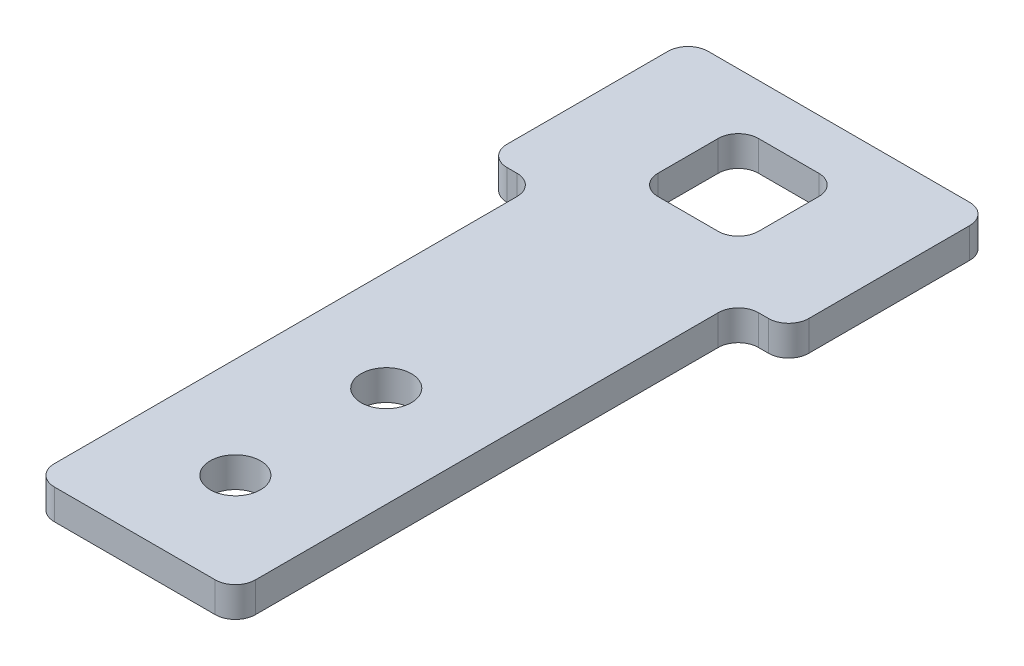
SolidWorks part; units mm, degrees
ref_plane "前视基准面" through (0, 0, 0) normal (0, 0, 1) x (1, 0, 0)
ref_plane "上视基准面" through (0, 0, 0) normal (0, 1, 0) x (1, 0, 0)
ref_plane "右视基准面" through (0, 0, 0) normal (1, 0, 0) x (0, 0, -1)
sketch "草图1" plane through (0, 0, 0) normal (0, 1, 0) x (1, 0, 0)
  line L0 (22, 50) -> (23, 50)
  line L1 (0, 70) -> (20, 70)
  line L2 (0, 48) -> (0, 2)
  line L3 (2, 0) -> (18, 0)
  line L4 (20, 48) -> (20, 2)
  line L5 (-3, 70) -> (23, 70)
  line L6 (-5, 68) -> (-5, 52)
  line L7 (-3, 50) -> (-2, 50)
  line L8 (25, 68) -> (25, 52)
  line L10 (7, 65) -> (13, 65)
  line L11 (5, 63) -> (5, 57)
  line L12 (7, 55) -> (13, 55)
  line L13 (15, 63) -> (15, 57)
  circle A0 centre (10, 25) radius 2.5
  circle A1 centre (10, 10) radius 2.5
  arc A2 (25, 68) -> (23, 70) centre (23, 68) ccw
  arc A3 (23, 50) -> (25, 52) centre (23, 52) ccw
  arc A4 (20, 48) -> (22, 50) centre (22, 48) cw
  arc A5 (18, 0) -> (20, 2) centre (18, 2) ccw
  arc A6 (0, 2) -> (2, 0) centre (2, 2) ccw
  arc A7 (-2, 50) -> (0, 48) centre (-2, 48) cw
  arc A8 (-5, 52) -> (-3, 50) centre (-3, 52) ccw
  arc A9 (-3, 70) -> (-5, 68) centre (-3, 68) ccw
  arc A10 (15, 63) -> (13, 65) centre (13, 63) ccw
  arc A11 (13, 55) -> (15, 57) centre (13, 57) ccw
  arc A12 (7, 55) -> (5, 57) centre (7, 57) cw
  arc A13 (5, 63) -> (7, 65) centre (7, 63) cw
  point P21 (25, 70)
  point P30 (0, 0)
  point P35 (-5, 50)
  point P38 (-5, 70)
  point P41 (15, 65)
  point P46 (5, 55)
  point P49 (5, 65)
  dimension "D10" = 5
  dimension "D12" = 5
  dimension "D16" = 2
  dimension "D17" = 2
  dimension "D1" = 20
  dimension "D2" = 70
  dimension "D3" = 30
  dimension "D4" = 20
  dimension "D5" = 5
  dimension "D6" = 10
  dimension "D7" = 10
  dimension "D8" = 5
  dimension "D9" = 10
  dimension "D11" = 10
  dimension "D13" = 10
  dimension "D14" = 10
  dimension "D15" = 15
extrude "凸台-拉伸1" add sketch "草图1" against normal blind 3 contours L8 L5 L1 L6 L7 L2 L3 L4 L0 L10 L13 L12 L11
